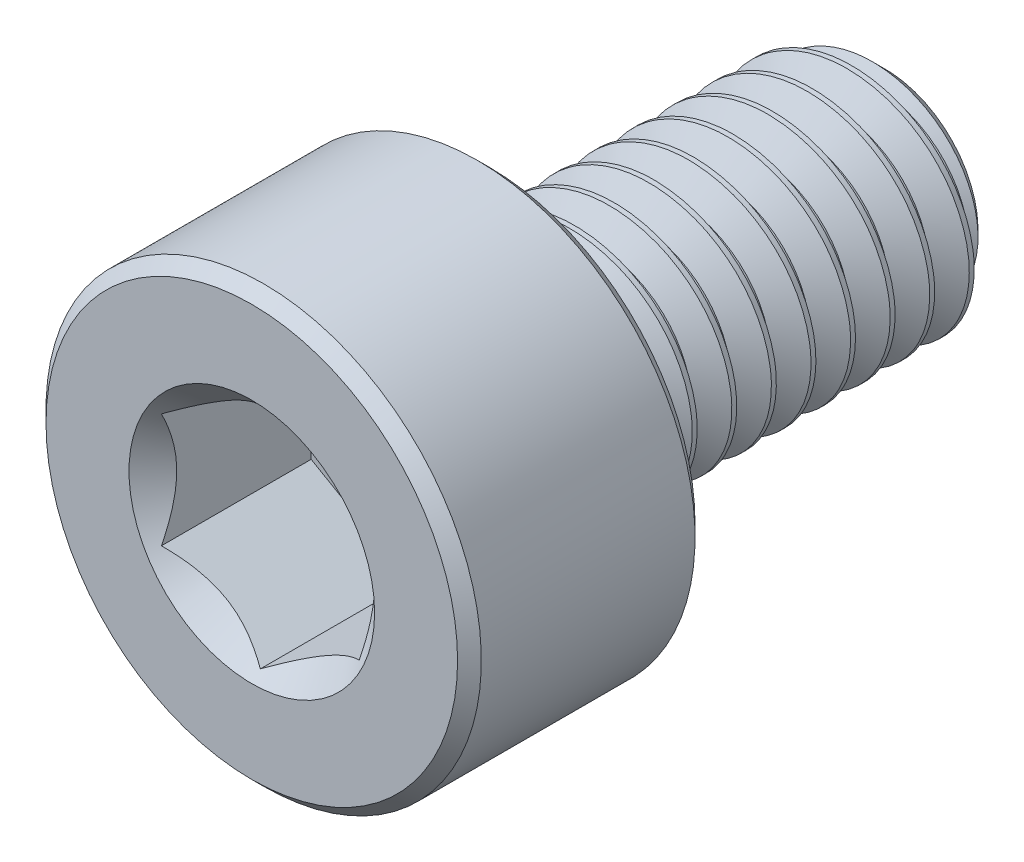
SolidWorks part; units mm, degrees
ref_plane "Front Plane" through (0, 0, 0) normal (0, 0, 1) x (1, 0, 0)
ref_plane "Top Plane" through (0, 0, 0) normal (0, 1, 0) x (1, 0, 0)
ref_plane "Right Plane" through (0, 0, 0) normal (1, 0, 0) x (0, 0, -1)
sketch "Sketch1" plane through (0, 0, 0) normal (1, 0, 0) x (0, 0, -1)
  line L0 (-4, 0) -> (4, 0) construction
  line L1 (4, 0) -> (4, 1.1752) construction
  line L2 (4, 1.1752) -> (3.6752, 1.5) construction
  line L3 (3.6752, 1.5) -> (3.625, 1.5) construction
  line L4 (3.625, 1.5) -> (-1, 1.5) construction
  line L5 (-1, 1.5) -> (-1, 2.75) construction
  line L6 (-1, 2.75) -> (-4, 2.75) construction
  line L7 (-4, 2.75) -> (-4, 0) construction
  line L8 (4, 1.1752) -> (4, 1.5) construction
  line L9 (3.9688, 1.5541) -> (4.2188, 1.1211) construction
  line L10 (4.2188, 1.1211) -> (4.4688, 1.5541) construction
  line L11 (4.4688, 1.5541) -> (3.9688, 1.5541) construction
  line L12 (4.2188, 1.5541) -> (4.2188, 1.5) construction
  line L13 (4.2188, 1.1211) -> (4.2188, 1.1752) construction
  line L14 (4.1875, 1.1752) -> (4.25, 1.1752) construction
  line L15 (4, 1.5) -> (4.4375, 1.5) construction
  line L16 (3.9844, 1.5271) -> (4.4531, 1.5271) construction
  line L17 (4, 0) -> (4, -1.5) construction
  line L18 (-1.15, 2.75) -> (-1, 2.6) construction
  line L19 (-3.85, 2.75) -> (-4, 2.6) construction
  line L20 (-1, 1.5) -> (-1, 0) construction
  line L21 (-1, 0.75) -> (0.6667, 0.75) construction
  line L22 (0.6667, 0.75) -> (2.3333, 0.75) construction
  line L23 (2.3333, 0.75) -> (4, 0.75) construction
  line L24 (0.6667, 0.75) -> (0.6667, 1.5) construction
  line L25 (0.6667, 1.5) -> (0.6667, 2.75) construction
  line L26 (2.3333, 0.75) -> (2.3333, 2.75) construction
  point P0 (-4, 1.25)
  point P3 (2.75, 1.5)
  point P4 (0, 0)
  point P18 (2.3333, 1.5)
  point P22 (4.2188, 1.1752)
  point P24 (3.625, 1.5)
  point P25 (4.2188, 1.5)
  point P28 (4.2188, 1.5271)
  point P29 (2.75, -1.5)
  point P30 (0.6667, 1.5)
  point P31 (-2.5, 2.75)
  point P37 (-1.525, 2.75)
  point P38 (-3.775, 2.75)
  point P45 (0.6667, 0.75)
  point P46 (2.3333, 0.75)
  dimension "D2" = 0.0625
  dimension "D7" = 0.15
  dimension "D8" = 0.15
  dimension "D9" = 0.15
  dimension "D10" = 0.075
  dimension "D11" = 0.375
  dimension "Drive Size" = 2.5
  dimension "Head Diameter" = 5.5
  dimension "Head Height" = 3
  dimension "Thread Pitch" = 0.5
  dimension "Thread Dia" = 3
  dimension "Length" = 5
  dimension "D12" = 0.375
  dimension "D4" = 1.25
  dimension "D3" = 45
sketch "Sketch2" plane through (0, 0, 0) normal (1, 0, 0) x (0, 0, -1)
  line L0 (-4, 0) -> (-4, 2.6)
  line L1 (-3.85, 2.75) -> (-1.15, 2.75)
  line L2 (-1, 2.6) -> (-1, 1.65)
  line L4 (3.6752, 1.5) -> (4, 1.1752)
  line L5 (4, 1.1752) -> (4, 0)
  line L6 (-1, 2.75) -> (-4, 2.75) construction
  line L7 (4, 0) -> (-4, 0)
  line L8 (-3.85, 2.75) -> (-4, 2.6) construction
  line L10 (-3.85, 2.75) -> (-4, 2.6)
  line L14 (-1.15, 2.75) -> (-1, 2.6) construction
  line L16 (-1.15, 2.75) -> (-1, 2.6)
  line L17 (-1, 1.5) -> (-1, 2.75) construction
  line L19 (-0.85, 1.5) -> (3.6752, 1.5)
  line L20 (3.625, 1.5) -> (-1, 1.5) construction
  arc A1 (-1, 1.65) -> (-0.85, 1.5) centre (-0.85, 1.65) ccw
  dimension "D3" = 0.15
revolve "Revolve1" add sketch "Sketch2" angle 360 about L7
sketch "Sketch3" plane through (0, 0, 4) normal (0, 0, 1) x (1, 0, 0)
  line L1 (1.25, -0.7217) -> (1.25, 0.7217)
  line L2 (1.25, 0.7217) -> (0, 1.4434)
  line L3 (0, 1.4434) -> (-1.25, 0.7217)
  line L4 (-1.25, 0.7217) -> (-1.25, -0.7217)
  line L5 (-1.25, -0.7217) -> (0, -1.4434)
  line L6 (0, -1.4434) -> (1.25, -0.7217)
  circle A0 centre (0, 0) radius 1.25 construction
  circle A1 centre (0, 0) radius 2.75 construction
  circle A2 centre (0, 0) radius 2.75 construction
  circle A3 centre (0, 0) radius 1.4434 construction
  point P13 (0, 0)
  dimension "D1" = 2.8868
extrude "Cut-Extrude1" cut sketch "Sketch3" against normal offset from surface (2 mm away) 1 up to face at (0, 2.6, 1)
sketch "Sketch4" plane through (0, 0, 4) normal (0, 0, 1) x (1, 0, 0)
  circle A0 centre (0, 0) radius 1.5516
  dimension "D1" = 3.1033
extrude "Cut-Extrude2" cut sketch "Sketch4" against normal up to vertex (1.5 mm away) draft 45 up to point (0, 2.75, 2.5)
sketch "Sketch11" plane through (0, 0, 0) normal (1, 0, 0) x (0, 0, -1)
  line L0 (-4, 0) -> (4, 0) construction
  line L1 (-4, 0) -> (4, 0) construction
  line L2 (-0.0625, 0) -> (-0.0625, 1.5) construction
  line L3 (3.625, 1.5) -> (-1, 1.5) construction
  line L4 (3.0625, 0) -> (3.0625, 1.5) construction
  line L6 (4, 1.1752) -> (4, 1.5) construction
  point P2 (-0.0625, 0)
  point P3 (3.0625, 0)
  dimension "D1" = 0.9375
  dimension "D2" = 0.9375
sketch "Sketch6" plane through (0, 0, -4) normal (0, 0, -1) x (-1, 0, 0)
  circle A0 centre (0, 0) radius 1.5
curve "Helix/Spiral1" pitch 0.5 height 5.5 turns 11
sketch "Sketch10" plane through (0, 0, 0) normal (1, 0, 0) x (0, 0, -1)
  line L0 (-0.85, -2.75) -> (-0.85, 2.75)
  line L5 (-4, 0) -> (4, 0) construction
  line L6 (-0.85, 1.5) -> (-0.85, -1.5) construction
  point P3 (-0.85, 0)
split "Split1" trim tools "Sketch10" bodies to split 106 resulting bodies 114 115
sketch "Sketch7" plane through (0, 0, 0) normal (1, 0, 0) x (0, 0, -1)
  line L0 (3.9844, 1.5271) -> (4.4531, 1.5271)
  line L1 (4.4531, 1.5271) -> (4.25, 1.1752)
  line L2 (4.25, 1.1752) -> (4.1875, 1.1752)
  line L3 (4.1875, 1.1752) -> (3.9844, 1.5271)
sweep "Cut-Sweep1" cut profiles "Sketch7" path "Helix/Spiral1"
sketch "Sketch8" plane through (0, 0, 0) normal (1, 0, 0) x (0, 0, -1)
  line L0 (-1, 0) -> (-1, 1.5)
  line L1 (-0.85, -1.5) -> (-0.85, 1.5) construction
  line L2 (-1, 1.5) -> (-0.85, 1.5)
  line L4 (-0.85, 1.5) -> (0.016, 0)
  line L5 (0.016, 0) -> (-1, 0)
  line L6 (3.625, 1.5) -> (-1, 1.5) construction
  line L7 (-4, 0) -> (4, 0) construction
  dimension "D1" = 60
revolve "Revolve2" add sketch "Sketch8" angle 360 about L5
equation "\"D2@Sketch1\" = \"Thread Pitch@Sketch1\" / 8"
equation "\"D4@Helix/Spiral1\" = \"Thread Pitch@Sketch1\""
equation "\"D7@Sketch1\" = \"Head Height@Sketch1\" * .05"
equation "\"D8@Sketch1\"=\"D7@Sketch1\""
equation "\"D9@Sketch1\"=\"D7@Sketch1\""
equation "\"D10@Sketch1\"=\"D7@Sketch1\"/2"
equation "\"D11@Sketch1\"=\"D10@Sketch1\"*5"
equation "\"D4@Sketch1\"=\"Thread Pitch@Sketch1\"*2.5"
equation "\"D12@Sketch1\"=\"Thread Pitch@Sketch1\"*.75"
equation "\"D3@Helix/Spiral1\"=\"Length@Sketch1\"+\"Thread Pitch@Sketch1\""
equation "\"D3@Sketch2\"=\"Thread Dia@Sketch1\"*0.05"
equation "\"D1@Sketch11\"=\"Length@Sketch1\"*0.1875"
equation "\"D2@Sketch11\"=\"D1@Sketch11\""
equation "\"D1@Sketch4\"=\"D1@Sketch3\"*1.075"
